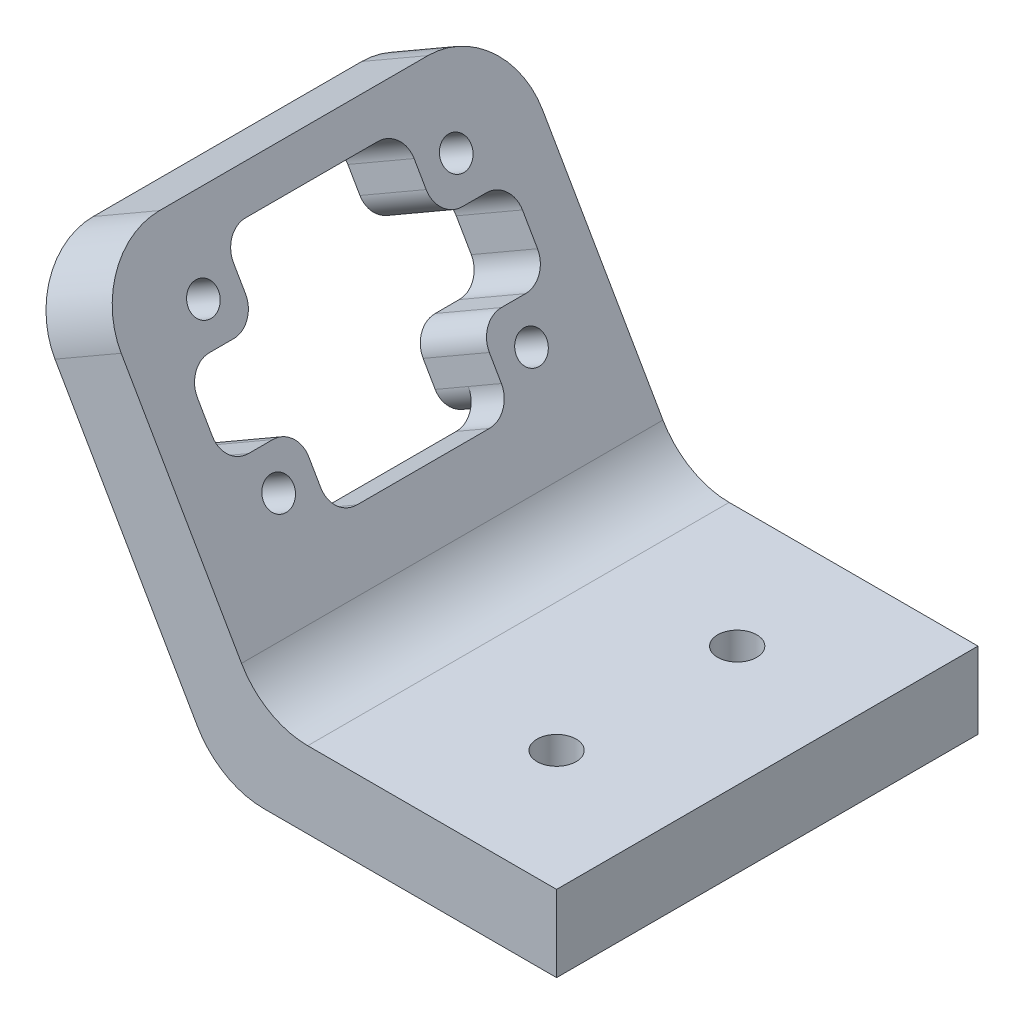
SolidWorks part; units mm, degrees
ref_plane "Front Plane" through (0, 0, 0) normal (0, 0, 1) x (1, 0, 0)
ref_plane "Top Plane" through (0, 0, 0) normal (0, 1, 0) x (1, 0, 0)
ref_plane "Right Plane" through (0, 0, 0) normal (1, 0, 0) x (0, 0, -1)
sketch "Sketch1" plane through (0, 0, 0) normal (0, 1, 0) x (1, 0, 0)
  line L0 (4, -7.5) -> (4, 7.5) construction
  line L1 (-14, -17.5) -> (14, -17.5)
  line L2 (-14, -17.5) -> (-14, 17.5)
  line L3 (-14, 17.5) -> (14, 17.5)
  line L4 (14, -17.5) -> (14, 17.5)
  line L5 (-14, -17.5) -> (14, 17.5) construction
  line L6 (-14, 17.5) -> (14, -17.5) construction
  line L7 (4, 0) -> (0, 0) construction
  circle A0 centre (4, 7.5) radius 1.625
  circle A1 centre (4, -7.5) radius 1.625
  point P0 (0, 0)
  point P9 (4, 0)
  dimension "D3" = 3.25
  dimension "D1" = 35
  dimension "D2" = 28
  dimension "D4" = 15
  dimension "D5" = 10
extrude "Boss-Extrude1" add sketch "Sketch1" along normal blind 6.35
sketch "Sketch2" plane through (0, 0, 17.5) normal (0, 0, 1) x (1, 0, 0)
  line L0 (-14, 0) -> (-30.8331, 29.1558)
  line L1 (-30.8331, 29.1558) -> (-25.3338, 32.3308)
  line L2 (-25.3338, 32.3308) -> (-10.3338, 6.35)
  line L3 (-14, 6.35) -> (14, 6.35) construction
  line L6 (-14, 6.35) -> (-14, 0) construction
  line L7 (-10.3338, 6.35) -> (-14, 0)
  dimension "D1" = 6.35
  dimension "D2" = 30
  dimension "D3" = 30
extrude "Boss-Extrude2" add sketch "Sketch2" against normal up to surface (35 mm away) up to face at (0, 3.175, -17.5)
sketch "Sketch3" plane through (-10.5, -6.0622, 0) normal (-0.866, -0.5, 0) x (0, 0, 1)
  line L0 (0, 7) -> (0, 40.6662) construction
  line L1 (-17.5, 7) -> (17.5, 7) construction
  line L2 (-17.5, 40.6662) -> (17.5, 40.6662) construction
  line L4 (-10.5, 22.1662) -> (10.5, 22.1662) construction
  line L5 (-10.5, 22.1662) -> (-10.5, 34.6662) construction
  line L6 (-10.5, 34.6662) -> (10.5, 34.6662) construction
  line L7 (10.5, 22.1662) -> (10.5, 34.6662) construction
  line L8 (-10.5, 22.1662) -> (10.5, 34.6662) construction
  line L9 (-10.5, 34.6662) -> (10.5, 22.1662) construction
  line L10 (-13.5, 25.1662) -> (13.5, 25.1662)
  line L11 (-13.5, 25.1662) -> (-13.5, 31.6662)
  line L12 (-13.5, 31.6662) -> (13.5, 31.6662)
  line L13 (13.5, 25.1662) -> (13.5, 31.6662)
  line L14 (-13.5, 25.1662) -> (13.5, 31.6662) construction
  line L15 (-13.5, 31.6662) -> (13.5, 25.1662) construction
  line L16 (-7.5, 19.1662) -> (7.5, 19.1662)
  line L17 (-7.5, 19.1662) -> (-7.5, 37.6662)
  line L18 (-7.5, 37.6662) -> (7.5, 37.6662)
  line L19 (7.5, 19.1662) -> (7.5, 37.6662)
  line L20 (-7.5, 19.1662) -> (7.5, 37.6662) construction
  line L21 (-7.5, 37.6662) -> (7.5, 19.1662) construction
  circle A0 centre (10.5, 34.6662) radius 1.25
  circle A1 centre (10.5, 22.1662) radius 1.25
  circle A2 centre (-10.5, 22.1662) radius 1.25
  circle A3 centre (-10.5, 34.6662) radius 1.25
  point P8 (0, 28.4162)
  point P16 (0, 28.4162)
  point P21 (0, 28.4162)
  dimension "D4" = 2.5
  dimension "D1" = 12.5
  dimension "D2" = 21
  dimension "D3" = 6
  dimension "D5" = 3
  dimension "D6" = 3
  dimension "D7" = 3
  dimension "D8" = 3
extrude "Cut-Extrude1" cut sketch "Sketch3" against normal blind 6.35 contours L10 L17 L12 L11 | L10 L19 L12 L17 | L12 L19 L18 L17 | A3 | A2 | A1 | A0 | L19 L10 L13 L12 | L16 L19 L10 L17
sketch "Sketch4" plane through (-10.5, -6.0622, 0) normal (-0.866, -0.5, 0) x (0, 0, 1)
  line L0 (0, 19.1662) -> (0, 7) construction
  line L1 (-7.5, 19.1662) -> (7.5, 19.1662) construction
  line L2 (-17.5, 7) -> (17.5, 7) construction
  line L3 (-13.5, 25.1662) -> (-13.5, 31.6662) construction
  line L4 (-13.5, -7) -> (13.5, -7)
  line L5 (-13.5, -7) -> (-13.5, 19.1662)
  line L6 (-13.5, 19.1662) -> (13.5, 19.1662)
  line L7 (13.5, -7) -> (13.5, 19.1662)
  line L8 (-13.5, -7) -> (13.5, 19.1662) construction
  line L9 (-13.5, 19.1662) -> (13.5, -7) construction
  line L10 (17.5, -7) -> (-17.5, -7) construction
  point P6 (0, 6.0831)
extrude "Cut-Extrude2" cut sketch "Sketch4" against normal blind 3.175
fillet "Fillet1" radius 2 14 edges at (-23.5835, 22.949, -7.5) (-23.5835, 22.949, -13.5) (-20.3335, 17.3199, -13.5) (-20.3335, 17.3199, -7.5) (-20.3335, 17.3199, 7.5) (-20.3335, 17.3199, 13.5) (-23.5835, 22.949, 13.5) (-23.5835, 22.949, 7.5) (-26.5835, 28.1452, 7.5) (-26.5835, 28.1452, -7.5) (-18.7083, 11.33, -13.5) (-18.7083, 11.33, 13.5) (-18.7083, 11.33, 7.5) (-18.7083, 11.33, -7.5)
fillet "Fillet2" radius 6.35 6 edges at (-14, 0, 15.5) (-14, 0, -15.5) (-10.3338, 6.35, 0) (-28.0835, 30.7433, 17.5) (-28.0835, 30.7433, -17.5) (-10.3338, 0, 0)
fillet "Fillet3" radius 2 2 edges at (-15.9586, 12.9175, 7.5) (-15.9586, 12.9175, -7.5)
